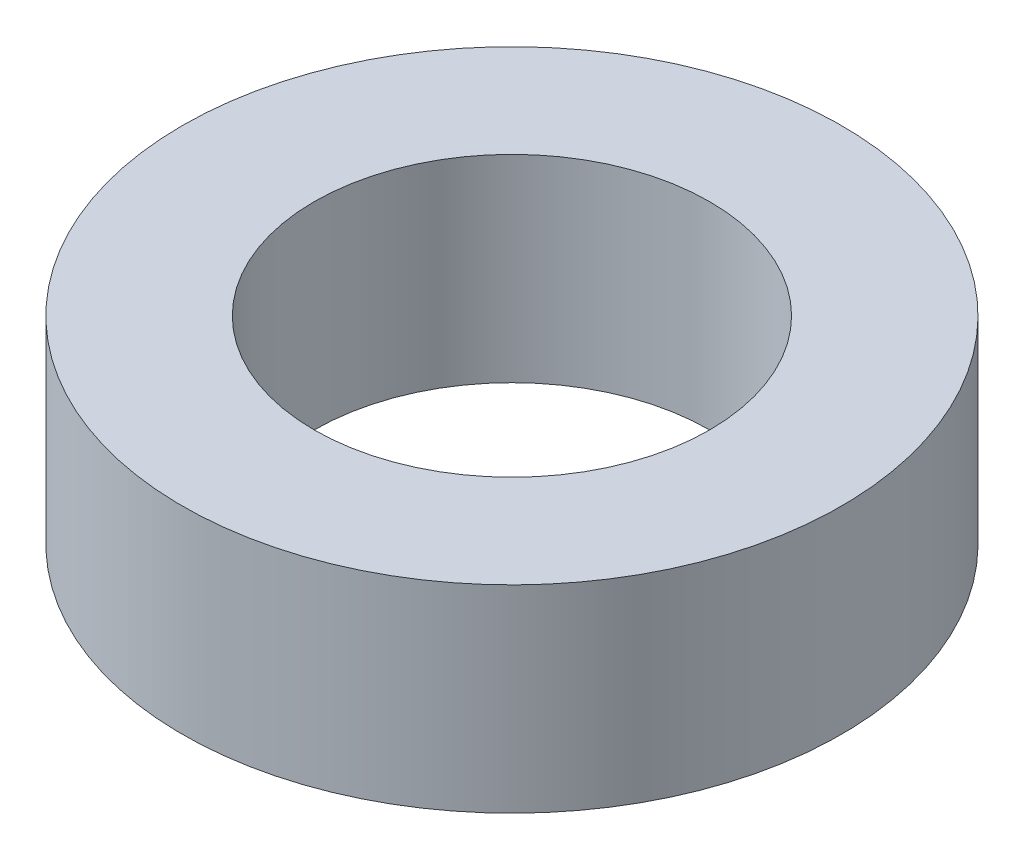
SolidWorks part; units mm, degrees
ref_plane "前视基准面" through (0, 0, 0) normal (0, 0, 1) x (1, 0, 0)
ref_plane "上视基准面" through (0, 0, 0) normal (0, 1, 0) x (1, 0, 0)
ref_plane "右视基准面" through (0, 0, 0) normal (1, 0, 0) x (0, 0, -1)
other "Configuration Table"
sketch "草图3" plane through (0, 0, 0) normal (0, 0, 1) x (1, 0, 0)
  line L0 (0, 15.6727) -> (0, -15.6727) construction
  line L1 (-25, 7.5) -> (-15, 7.5)
  line L2 (-25, 7.5) -> (-25, -7.5)
  line L3 (-25, -7.5) -> (-15, -7.5)
  line L4 (-15, 7.5) -> (-15, -7.5)
  line L5 (-25, 7.5) -> (-15, -7.5) construction
  line L6 (-25, -7.5) -> (-15, 7.5) construction
  point P0 (-20, 0)
  point P5 (0, 0)
  dimension "D1" = 20
  dimension "D2" = 15
  dimension "D3" = 10
revolve "旋转1" add sketch "草图3" angle 360 about L0
sketch "草图6" plane through (0, 0, 0) normal (0, 0, 1) x (1, 0, 0)
  line L0 (-6.0472, 2.6446) -> (4.9808, 2.6446)
  text T0 "空心圆柱"
